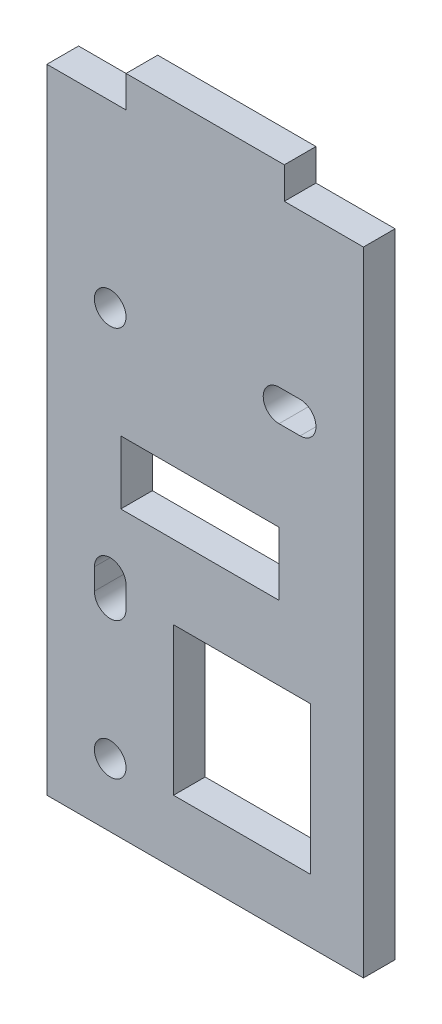
SolidWorks part; units mm, degrees
ref_plane "Front Plane" through (0, 0, 0) normal (0, 0, 1) x (1, 0, 0)
ref_plane "Top Plane" through (0, 0, 0) normal (0, 1, 0) x (1, 0, 0)
ref_plane "Right Plane" through (0, 0, 0) normal (1, 0, 0) x (0, 0, -1)
sketch "Sketch1" plane through (0, 0, 0) normal (0, 0, 1) x (1, 0, 0)
  line L0 (6, 0) -> (6, 60) construction
  line L1 (0, 0) -> (30, 0)
  line L2 (0, 0) -> (0, 60)
  line L3 (0, 60) -> (7.5, 60)
  line L4 (30, 0) -> (30, 60)
  line L6 (7.5, 60) -> (7.5, 63)
  line L7 (7.5, 63) -> (22.5, 63)
  line L8 (22.5, 60) -> (22.5, 63)
  line L9 (12, 20) -> (25, 20)
  line L10 (12, 20) -> (12, 6)
  line L11 (12, 6) -> (25, 6)
  line L12 (25, 20) -> (25, 6)
  line L13 (0, 43) -> (30, 43) construction
  line L14 (22.5, 60) -> (30, 60)
  line L15 (7, 33) -> (22, 33)
  line L16 (7, 33) -> (7, 27)
  line L17 (7, 27) -> (22, 27)
  line L18 (22, 33) -> (22, 27)
  line L19 (6, 21) -> (6, 19) construction
  line L20 (7.5, 21) -> (7.5, 19)
  line L21 (4.5, 21) -> (4.5, 19)
  line L22 (22, 43) -> (24, 43) construction
  line L23 (22, 44.5) -> (24, 44.5)
  line L24 (22, 41.5) -> (24, 41.5)
  circle A1 centre (6, 6) radius 1.5
  circle A2 centre (6, 43) radius 1.5
  arc A4 (7.5, 21) -> (4.5, 21) centre (6, 21) ccw
  arc A5 (4.5, 19) -> (7.5, 19) centre (6, 19) ccw
  arc A6 (22, 44.5) -> (22, 41.5) centre (22, 43) ccw
  arc A7 (24, 41.5) -> (24, 44.5) centre (24, 43) ccw
  point P23 (0, 0)
  point P24 (0, 0)
  point P31 (6, 20)
  point P36 (23, 43)
  point P41 (0, 0)
  point P42 (25.3886, 32.816)
  point P43 (0, 0)
  point P44 (0, 0)
  point P45 (0, 0)
  dimension "D11" = 1
  dimension "D12" = 3
  dimension "D16" = 2
  dimension "D17" = 3
  dimension "D21" = 0
  dimension "D10" = 17
  dimension "D18" = 6
  dimension "D1" = 60
  dimension "D2" = 30
  dimension "D3" = 15
  dimension "D4" = 7.5
  dimension "D5" = 3
  dimension "D6" = 6
  dimension "D7" = 13
  dimension "D8" = 14
  dimension "D9" = 6
  dimension "D13" = 6
  dimension "D14" = 1
  dimension "D15" = 6
  dimension "D19" = 10
  dimension "D20" = 0
extrude "Boss-Extrude1" add sketch "Sketch1" along normal blind 3
